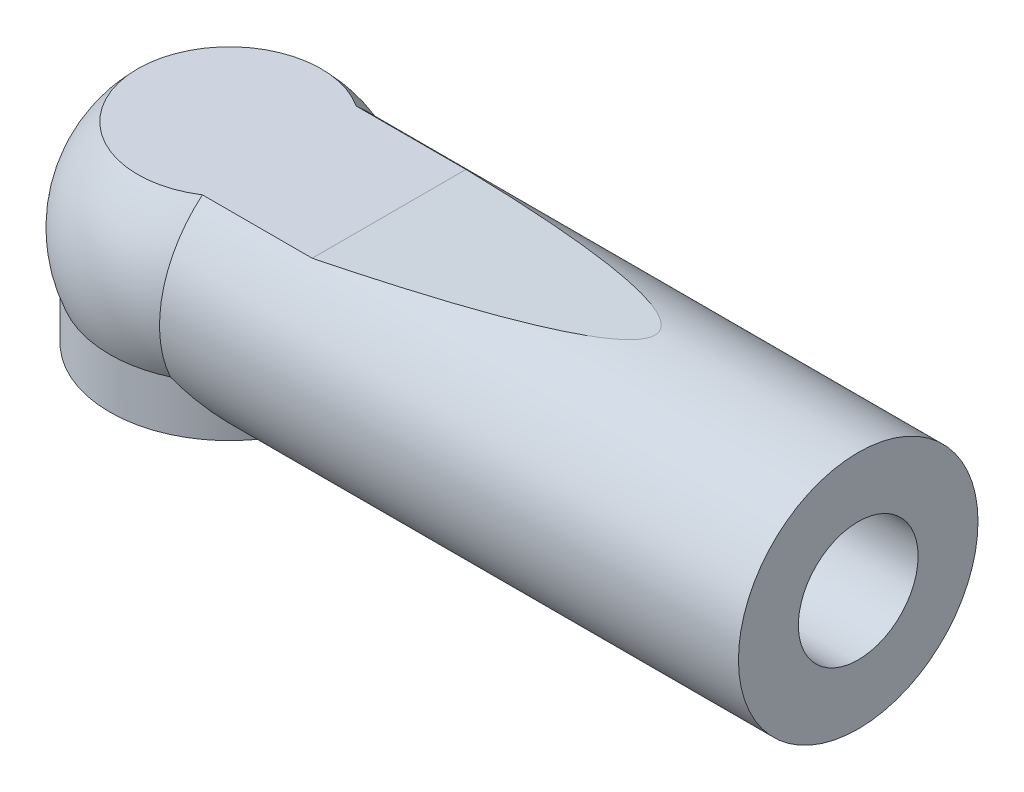
SolidWorks part; units mm, degrees
ref_plane "Plan de face" through (0, 0, 0) normal (0, 0, 1) x (1, 0, 0)
ref_plane "Plan de dessus" through (0, 0, 0) normal (0, 1, 0) x (1, 0, 0)
ref_plane "Plan de droite" through (0, 0, 0) normal (1, 0, 0) x (0, 0, -1)
sketch "Esquisse1" plane through (0, 0, 0) normal (0, 0, 1) x (1, 0, 0)
  line L0 (0, 3.25) -> (0, -3.25)
  arc A0 (0, 3.25) -> (0, -3.25) centre (0, 0) ccw
  dimension "D1" = 6.5
revolve "Révolution1" add sketch "Esquisse1" angle 360 about L0
sketch "Esquisse2" plane through (0, 0, 0) normal (1, 0, 0) x (0, 0, -1)
  circle A0 centre (0, 0) radius 3
  dimension "D1" = 6
extrude "Boss.-Extru.1" add sketch "Esquisse2" along normal blind 15.75
sketch "Esquisse3" plane through (15.75, 0, 0) normal (1, 0, 0) x (0, 0, -1)
  circle A0 centre (0, 0) radius 1.5
  dimension "D1" = 3
extrude "Enlèv. mat.-Extru.1" cut sketch "Esquisse3" against normal blind 12
sketch "Esquisse4" plane through (0, 0, 0) normal (0, 0, 1) x (1, 0, 0)
  line L1 (-2.2962, 2.3) -> (4, 2.3)
  line L2 (-2.2962, 2.3) -> (-2.2962, 3.25)
  line L3 (-2.2962, 3.25) -> (13.0386, 3.25)
  line L4 (4, 2.3) -> (13.0386, 3.25)
  line L5 (-2.2962, -2.3) -> (4, -2.3)
  line L6 (-2.2962, -2.3) -> (-2.2962, -3.25)
  line L7 (-2.2962, -3.25) -> (7.5454, -3.25)
  line L8 (4, -2.3) -> (7.5454, -3.25)
  line L10 (15.75, 3) -> (1.25, 3) construction
  line L11 (15.75, 3) -> (10.6601, 3) construction
  line L12 (1.25, -3) -> (15.75, -3) construction
  line L13 (6.6124, -3) -> (15.75, -3) construction
  arc A0 (1.25, 3) -> (1.25, -3) centre (0, 0) ccw construction
  dimension "D1" = 2.3
  dimension "D2" = 2.3
  dimension "D3" = 4
  dimension "D4" = 4
  dimension "D5" = 6
  dimension "D6" = 15
extrude "Enlèv. mat.-Extru.2" cut sketch "Esquisse4" against normal mid plane 12
sketch "Esquisse5" plane through (0, 0, 0) normal (0, 1, 0) x (1, 0, 0)
  circle A0 centre (0, 0) radius 3
  dimension "D1" = 6
extrude "Boss.-Extru.2" add sketch "Esquisse5" against normal blind 2.5
sketch "Esquisse6" plane through (0, 0, 0) normal (0, 0, 1) x (1, 0, 0)
  line L0 (1.75, -0.9682) -> (1.75, -2.5)
  line L1 (1.75, -2.5) -> (0, -2.5)
  line L2 (-3, -2.5) -> (3, -2.5) construction
  line L3 (0, -2.5) -> (0, 2)
  arc A0 (1.75, -0.9682) -> (0, 2) centre (0, 0) ccw
  dimension "D1" = 4
  dimension "D2" = 1.75
revolve "Enlèvement de matière-Révolution1" cut sketch "Esquisse6" angle 360 about L3
